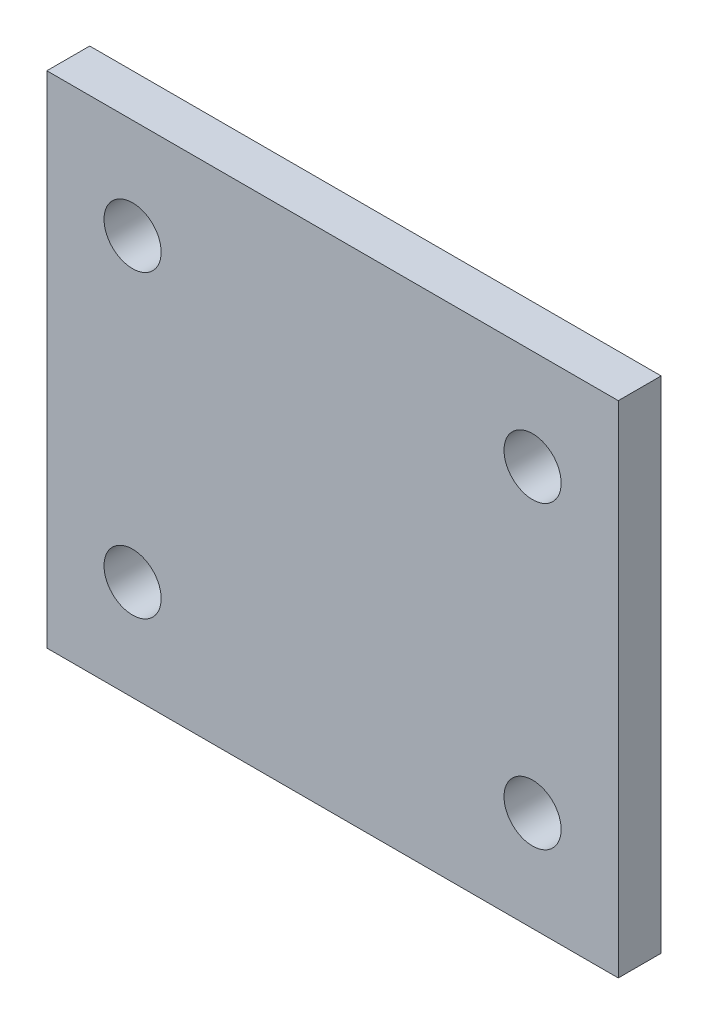
SolidWorks part; units mm, degrees
ref_plane "Front Plane" through (0, 0, 0) normal (0, 0, 1) x (1, 0, 0)
ref_plane "Top Plane" through (0, 0, 0) normal (0, 1, 0) x (1, 0, 0)
ref_plane "Right Plane" through (0, 0, 0) normal (1, 0, 0) x (0, 0, -1)
sketch "Sketch1" plane through (0, 0, 0) normal (0, 0, 1) x (1, 0, 0)
  line L1 (17.6103, 30.1961) -> (-22.3897, 30.1961)
  line L2 (17.6103, 30.1961) -> (17.6103, -4.8039)
  line L3 (17.6103, -4.8039) -> (-22.3897, -4.8039)
  line L4 (-22.3897, 30.1961) -> (-22.3897, -4.8039)
  line L5 (17.6103, 30.1961) -> (-22.3897, -4.8039) construction
  line L6 (17.6103, -4.8039) -> (-22.3897, 30.1961) construction
  point P0 (-2.3897, 12.6961)
  dimension "D1" = 35
  dimension "D2" = 40
extrude "Boss-Extrude1" add sketch "Sketch1" along normal blind 3
sketch "Sketch2" plane through (0, 0, 3) normal (0, 0, 1) x (1, 0, 0)
  circle A0 centre (-16.3897, 23.1961) radius 2
  circle A1 centre (-16.3897, 2.1961) radius 2
  circle A2 centre (11.6103, 2.1961) radius 2
  circle A3 centre (11.6103, 23.1961) radius 2
  dimension "D1" = 4
  dimension "D2" = 4
  dimension "D3" = 4
  dimension "D4" = 4
extrude "Cut-Extrude1" cut sketch "Sketch2" against normal blind 3
